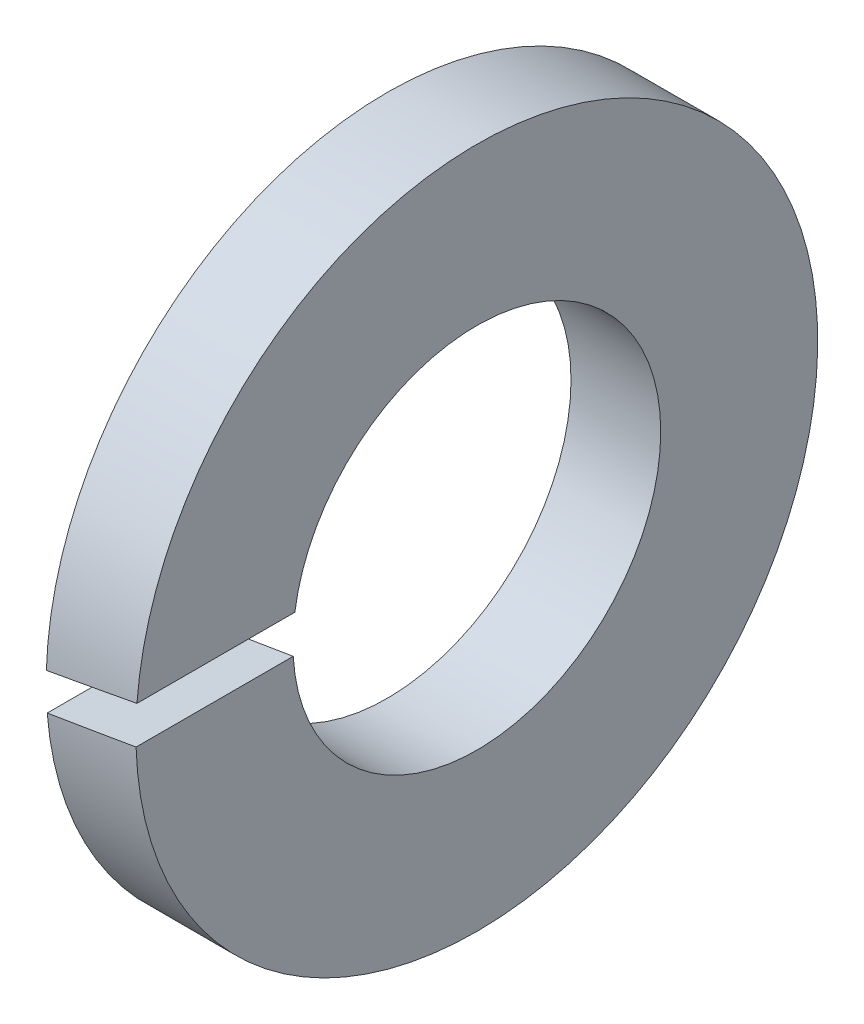
SolidWorks part; units mm, degrees
ref_plane "Front Plane" through (0, 0, 0) normal (0, 0, 1) x (1, 0, 0)
ref_plane "Top Plane" through (0, 0, 0) normal (0, 1, 0) x (1, 0, 0)
ref_plane "Right Plane" through (0, 0, 0) normal (1, 0, 0) x (0, 0, -1)
sketch "Sketch1" plane through (0, 0, 0) normal (0, 0, 1) x (1, 0, 0)
  line L0 (-1, 0) -> (0, 0) construction
  line L2 (-1, 2.05) -> (0, 2.05)
  line L3 (-1, 2.05) -> (-1, 3.8)
  line L4 (-1, 3.8) -> (0, 3.8)
  line L5 (0, 2.05) -> (0, 3.8)
  dimension "MSM_123" = 1
  dimension "MSM_124" = 7.6
  dimension "MSM_125" = 4.1
revolve "Revolve1" add sketch "Sketch1" angle 360 about L0
sketch "Sketch2" plane through (0, 0, 0) normal (0, 0, 1) x (1, 0, 0)
  line L0 (-1, 0.12) -> (0, 0.2963)
  line L1 (0, -0.12) -> (-1, -0.2963)
  line L2 (0, -0.12) -> (0, 0.2963)
  line L3 (-1, 0.12) -> (-1, -0.2963)
  line L4 (-1, 0.12) -> (0, -0.12) construction
  point P4 (-0.5, 0)
  dimension "MSM_123" = 1
  dimension "FIX_2" = 0.41
  dimension "FIX_3" = 80
extrude "Cut-Extrude1" cut sketch "Sketch2" along normal through all
equation "\"FIX_2@Sketch2\"= \"MSM_125@Sketch1\" * 0.1"
